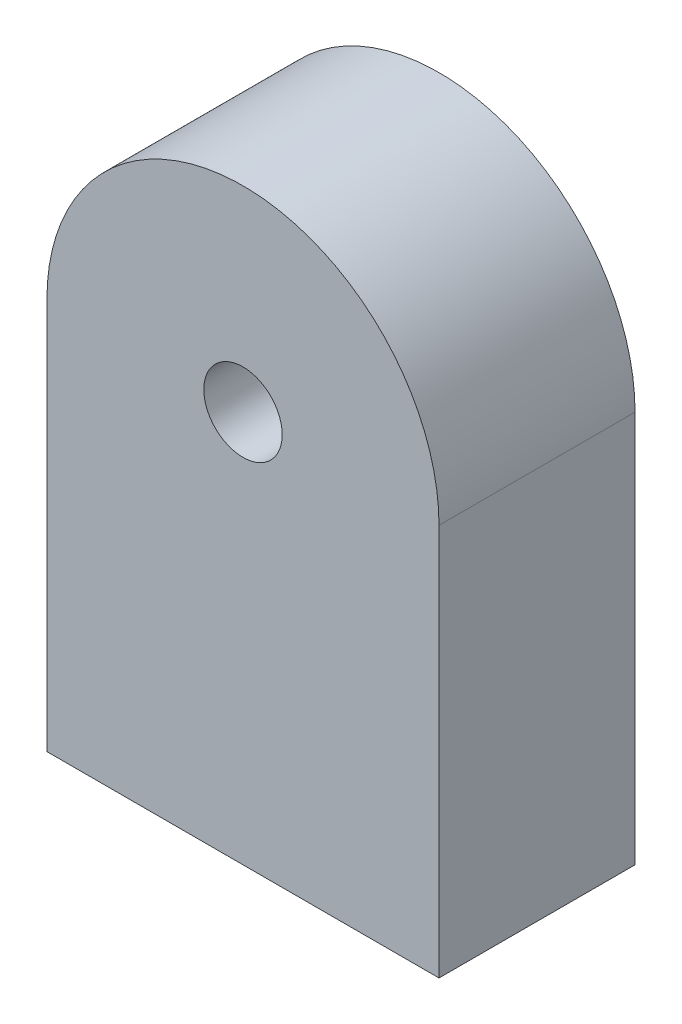
SolidWorks part; units mm, degrees
ref_plane "Alzado" through (0, 0, 0) normal (0, 0, 1) x (1, 0, 0)
ref_plane "Planta" through (0, 0, 0) normal (0, 1, 0) x (1, 0, 0)
ref_plane "Vista lateral" through (0, 0, 0) normal (1, 0, 0) x (0, 0, -1)
sketch "Croquis2" plane through (0, 0, 0) normal (0, 0, 1) x (1, 0, 0)
  line L1 (0, 0) -> (-30, 0)
  line L2 (0, 0) -> (0, 30)
  line L4 (-30, 0) -> (-30, 30)
  arc A0 (0, 30) -> (-30, 30) centre (-15, 30) ccw
  dimension "D1" = 30
  dimension "D2" = 30
extrude "Saliente-Extruir1" add sketch "Croquis2" along normal mid plane 15
sketch "Croquis3" plane through (0, 0, 7.5) normal (0, 0, 1) x (1, 0, 0)
  circle A0 centre (-15, 30) radius 3
  dimension "D1" = 6
extrude "Cortar-Extruir1" cut sketch "Croquis3" against normal through all
